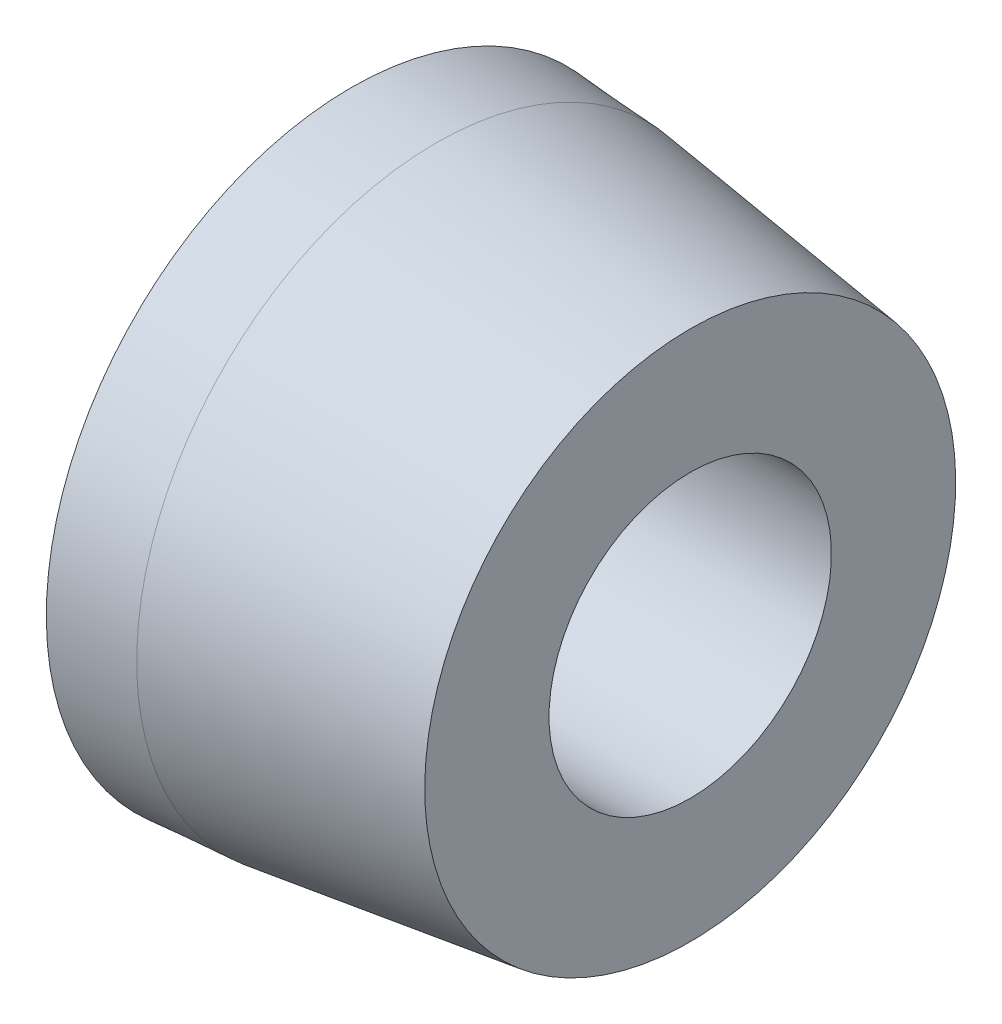
SolidWorks part; units mm, degrees
ref_plane "Front Plane" through (0, 0, 0) normal (0, 0, 1) x (1, 0, 0)
ref_plane "Top Plane" through (0, 0, 0) normal (0, 1, 0) x (1, 0, 0)
ref_plane "Right Plane" through (0, 0, 0) normal (1, 0, 0) x (0, 0, -1)
sketch "Sketch1" plane through (0, 0, 0) normal (0, 0, 1) x (1, 0, 0)
  line L0 (0, 0) -> (3000, 0) construction
  line L1 (1250, 250) -> (1250, 540)
  line L2 (1250, 540) -> (1400, 530)
  line L3 (1400, 530) -> (1550, 510)
  line L4 (1550, 510) -> (1700, 490)
  line L5 (1700, 490) -> (1850, 470)
  line L6 (1850, 470) -> (1850, 250)
  line L7 (1850, 250) -> (1250, 250)
revolve "Revolve1" add sketch "Sketch1" angle 360 about L0
